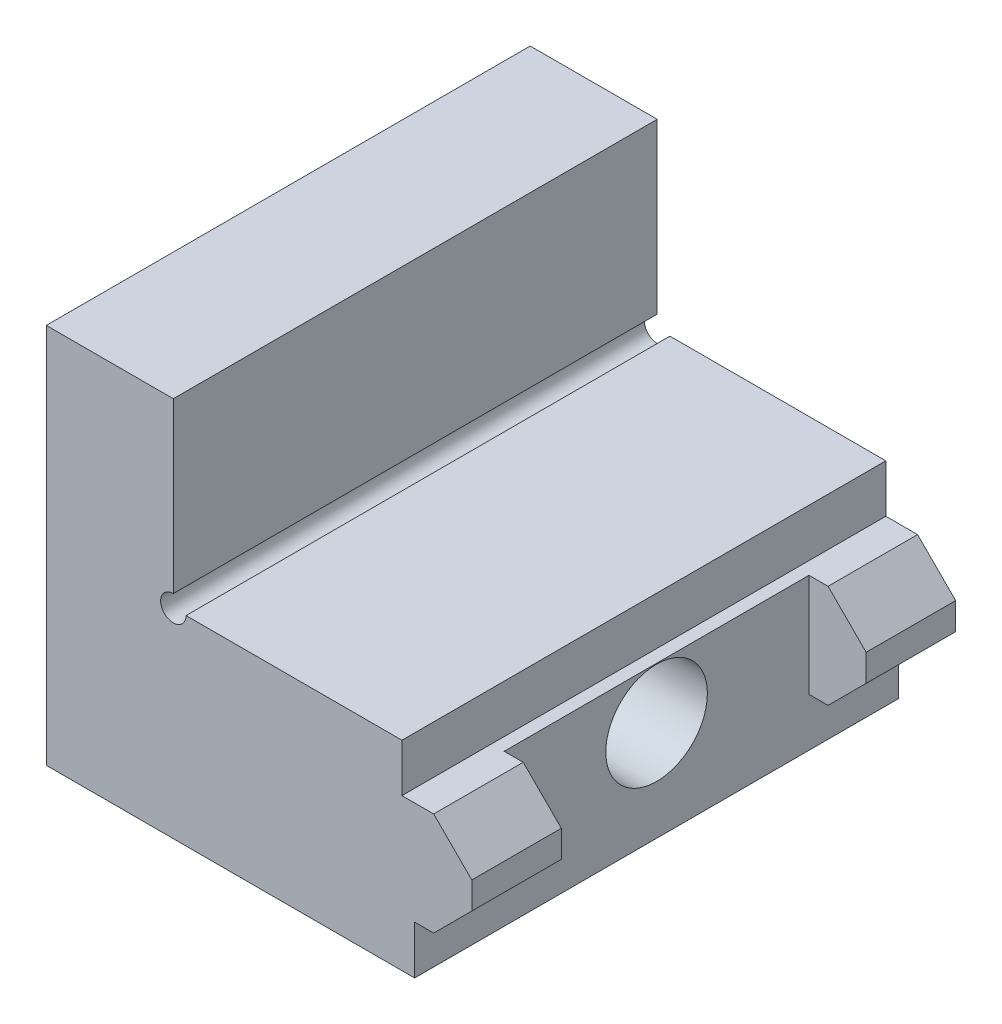
SolidWorks part; units mm, degrees
ref_plane "Front Plane" through (0, 0, 0) normal (0, 0, 1) x (1, 0, 0)
ref_plane "Top Plane" through (0, 0, 0) normal (0, 1, 0) x (1, 0, 0)
ref_plane "Right Plane" through (0, 0, 0) normal (1, 0, 0) x (0, 0, -1)
sketch "Sketch1" plane through (0, 0, 0) normal (0, 0, 1) x (1, 0, 0)
  line L0 (-10, -15.715) -> (-10, 14.285)
  line L1 (-10, 14.285) -> (0, 14.285)
  line L2 (0, 14.285) -> (0, 1)
  line L3 (1, 0) -> (18, 0)
  line L4 (18, 0) -> (18, -3.78)
  line L5 (19, -15.715) -> (-10, -15.715)
  line L6 (0, 1) -> (0, 0) construction
  line L7 (0, 0) -> (1, 0) construction
  line L8 (18, -3.78) -> (23.5, -3.78)
  line L9 (23.5, -3.78) -> (23.5, -11.9)
  line L10 (23.5, -11.9) -> (19, -11.9)
  line L11 (21.2322, -7.84) -> (23.5, -7.84) construction
  line L12 (19, -11.9) -> (19, -15.715)
  arc A0 (0, 1) -> (1, 0) centre (0, 0) ccw
  dimension "D4" = 2
  dimension "D1" = 18
  dimension "D2" = 10
  dimension "D3" = 30
  dimension "D5" = 15.715
  dimension "D6" = 8.12
  dimension "D7" = 4.5
  dimension "D8" = 3.815
  dimension "D9" = 19
extrude "Boss-Extrude1" add sketch "Sketch1" against normal blind 38.1 contours A0 L2 L1 L0 L5 L4 L3 | L10 L9 L8 L4
sketch "Sketch2" plane through (0, 0, 0) normal (1, 0, 0) x (0, 0, -1)
  line L0 (-19.05, -7.84) -> (19.05, -7.84) construction
  line L1 (0, -7.84) -> (-19.05, -7.84) construction
  line L2 (0, -3.78) -> (0, -11.9) construction
  line L3 (0, 0) -> (0, -7.84) construction
  circle A0 centre (-19.05, -7.84) radius 4
  circle A1 centre (19.05, -7.84) radius 4
  dimension "D4" = 8
  dimension "D3" = 38.1
extrude "Cut-Extrude1" cut sketch "Sketch2" along normal blind 55.4 and the other way blind 30
sketch "Sketch3" plane through (0, 0, 0) normal (1, 0, 0) x (0, 0, -1)
  line L0 (19.05, -7.84) -> (0, -7.84) construction
  line L1 (0, -3.78) -> (0, -11.9) construction
  line L2 (0, -7.84) -> (0, 0) construction
  line L3 (19.05, -7.84) -> (19.05, -15.715) construction
  line L4 (38.1, -15.715) -> (0, -15.715) construction
  circle A1 centre (19.05, -7.84) radius 6.5
  dimension "D1" = 13
extrude "Cut-Extrude2" cut sketch "Sketch3" against normal blind 18.2
sketch "Sketch4" plane through (0, 0, 0) normal (1, 0, 0) x (0, 0, -1)
  line L0 (19.05, -7.84) -> (19.05, -15.715) construction
  line L1 (0, -3.78) -> (0, -11.9) construction
  line L2 (38.1, -15.715) -> (0, -15.715) construction
  line L7 (19.05, -7.84) -> (0, -7.84) construction
  line L9 (7.05, 2.16) -> (31.05, 2.16)
  line L10 (7.05, 2.16) -> (7.05, -17.84)
  line L11 (7.05, -17.84) -> (31.05, -17.84)
  line L12 (31.05, 2.16) -> (31.05, -17.84)
  line L13 (7.05, 2.16) -> (31.05, -17.84) construction
  line L14 (7.05, -17.84) -> (31.05, 2.16) construction
  dimension "D2" = 24
  dimension "D4" = 20
extrude "Cut-Extrude3" cut sketch "Sketch4" along normal blind 10 from surface at 19 starting at face at (19, -13.8075, -19.05)
chamfer "Chamfer1" distance 3 angle 45 4 edges at (23.5, -11.9, -34.575) (23.5, -11.9, -3.525) (23.5, -3.78, -34.575) (23.5, -3.78, -3.525)
